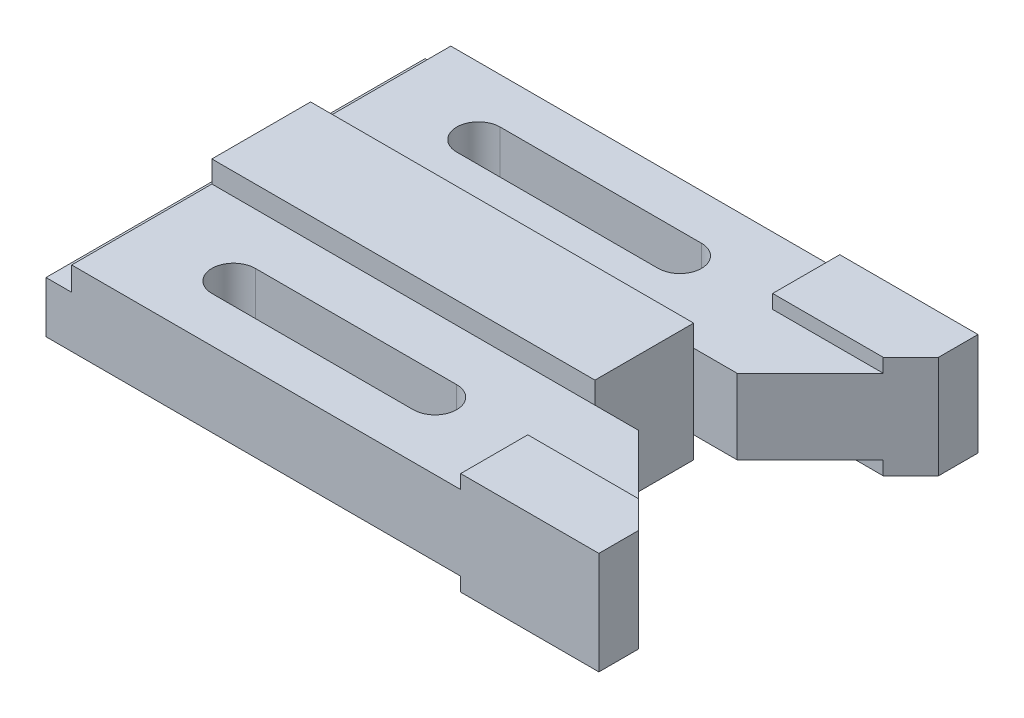
SolidWorks part; units mm, degrees
material "1060 Alloy"
ref_plane "Front Plane" through (0, 0, 0) normal (0, 0, 1) x (1, 0, 0)
ref_plane "Top Plane" through (0, 0, 0) normal (0, 1, 0) x (1, 0, 0)
ref_plane "Right Plane" through (0, 0, 0) normal (1, 0, 0) x (0, 0, -1)
sketch "Sketch2" plane through (0, 0, 0) normal (0, 1, 0) x (1, 0, 0)
  line L0 (0, 0) -> (105, 0) construction
  line L19 (140, 38) -> (114.5, 12.5)
  line L26 (0, -48) -> (0, 48)
  line L27 (0, 48) -> (140, 48)
  line L30 (140, 38) -> (140, 48)
  line L33 (114.5, 12.5) -> (105, 12.5)
  line L35 (105, 12.5) -> (105, -12.5)
  line L36 (140, 0) -> (146.2315, 0) construction
  line L37 (30.5, 31) -> (81.5, 31) construction
  line L38 (140, 48) -> (98, 48)
  line L39 (140, 48) -> (140, 38)
  line L40 (133, 31) -> (98, 31)
  line L41 (98, 48) -> (98, 31)
  line L42 (30.5, 36.5) -> (81.5, 36.5)
  line L43 (30.5, 25.5) -> (81.5, 25.5)
  line L44 (30.5, -31) -> (81.5, -31) construction
  line L45 (30.5, -36.5) -> (81.5, -36.5)
  line L46 (30.5, -25.5) -> (81.5, -25.5)
  line L47 (98, -48) -> (98, -31)
  line L48 (133, -31) -> (98, -31)
  line L49 (140, -38) -> (140, -48)
  line L50 (140, -38) -> (114.5, -12.5)
  line L51 (114.5, -12.5) -> (105, -12.5)
  line L52 (0, -48) -> (140, -48)
  arc A0 (30.5, 36.5) -> (30.5, 25.5) centre (30.5, 31) ccw
  arc A1 (81.5, 25.5) -> (81.5, 36.5) centre (81.5, 31) ccw
  arc A2 (30.5, -36.5) -> (30.5, -25.5) centre (30.5, -31) cw
  arc A3 (81.5, -25.5) -> (81.5, -36.5) centre (81.5, -31) cw
  point P14 (56, 31)
  point P21 (56, -31)
  point P34 (109.75, -12.5)
  dimension "D10" = 51
  dimension "D12" = 10
  dimension "D9" = 5.5
  dimension "D11" = 30.5
  dimension "D17" = 30.5
  dimension "D20" = 36.416
  dimension "D1" = 140
  dimension "D2" = 48
  dimension "D3" = 10
  dimension "D4" = 35
  dimension "D5" = 17
  dimension "D6" = 35.5
  dimension "D7" = 45
  dimension "D8" = 105
  dimension "D13" = 25.5
  dimension "D14" = 9.5
  dimension "D15" = 51
  dimension "D16" = 11.5
  dimension "D18" = 35
  dimension "D19" = 17
  dimension "D21" = 90
  dimension "D22" = 109.75
  dimension "D23" = 98
  dimension "D24" = 62
extrude "Boss-Extrude1" add sketch "Sketch2" along normal blind 30 contours L26 L52 L47 L48 L50 L51 L35 L33 L19 L40 L41 L27 A1 L43 A0 L42 L46 A3 L45 A2 | L27 L41 L40 L19 L30 | L47 L52 L49 L50 L48
sketch "Sketch3" plane through (0, 30, 0) normal (0, 1, 0) x (1, 0, 0)
  line L0 (105, 48) -> (105, 31)
  line L1 (0, 48) -> (140, 48) construction
  line L2 (105, 31) -> (133, 31)
  line L3 (140, 38) -> (114.5, 12.5) construction
  line L4 (133, 31) -> (140, 38)
  line L5 (140, 38) -> (140, 48)
  line L6 (140, 48) -> (105, 48)
  line L7 (0, 0) -> (32.5584, 0) construction
  line L8 (140, -38) -> (140, -48)
  line L9 (140, -48) -> (105, -48)
  line L10 (105, -48) -> (105, -31)
  line L11 (105, -31) -> (133, -31)
  line L12 (133, -31) -> (140, -38)
  dimension "D1" = 35
  dimension "D2" = 17
extrude "Cut-Extrude1" cut sketch "Sketch3" against normal blind 2
sketch "Sketch4" plane through (0, 0, 0) normal (0, -1, 0) x (1, 0, 0)
  line L0 (105, 48) -> (105, 31)
  line L1 (0, 48) -> (140, 48) construction
  line L2 (105, 31) -> (133, 31)
  line L3 (140, 38) -> (114.5, 12.5) construction
  line L4 (133, 31) -> (140, 38)
  line L5 (140, 38) -> (140, 48)
  line L6 (140, 48) -> (105, 48)
  line L7 (0, 0) -> (27.9707, 0) construction
  line L8 (105, -48) -> (105, -31)
  line L9 (140, -48) -> (105, -48)
  line L10 (140, -38) -> (140, -48)
  line L11 (133, -31) -> (140, -38)
  line L12 (105, -31) -> (133, -31)
  dimension "D1" = 35
  dimension "D2" = 17
extrude "Cut-Extrude2" cut sketch "Sketch4" against normal blind 2
sketch "Sketch5" plane through (0, 30, 0) normal (0, 1, 0) x (1, 0, 0)
  line L0 (0, -48) -> (105, -48) construction
  line L1 (0, 48) -> (6.5, 48)
  line L2 (0, 48) -> (0, -48)
  line L3 (0, -48) -> (6.5, -48)
  line L4 (6.5, 48) -> (6.5, -48)
  dimension "D1" = 6.5
extrude "Cut-Extrude3" cut sketch "Sketch5" against normal blind 11.5
sketch "Sketch6" plane through (0, 30, 0) normal (0, 1, 0) x (1, 0, 0)
  line L0 (105, 12.5) -> (6.5, 12.5)
  line L1 (6.5, -48) -> (6.5, 48) construction
  line L2 (105, -12.5) -> (6.5, -12.5)
  line L3 (6.5, -48) -> (6.5, 48) construction
  line L4 (6.5, -12.5) -> (6.5, -48)
  line L5 (6.5, -48) -> (105, -48)
  line L6 (105, -48) -> (105, -31)
  line L7 (105, -31) -> (133, -31)
  line L8 (133, -31) -> (114.5, -12.5)
  line L9 (114.5, -12.5) -> (105, -12.5)
  line L10 (105, 12.5) -> (114.5, 12.5)
  line L11 (114.5, 12.5) -> (133, 31)
  line L12 (133, 31) -> (105, 31)
  line L13 (105, 31) -> (105, 48)
  line L14 (105, 48) -> (6.5, 48)
  line L15 (6.5, 48) -> (6.5, 12.5)
extrude "Cut-Extrude4" cut sketch "Sketch6" against normal blind 5.5
sketch "Sketch7" plane through (0, 0, 0) normal (0, -1, 0) x (1, 0, 0)
  line L0 (105, 12.5) -> (6.5, 12.5)
  line L1 (6.5, 12.5) -> (6.5, -12.5)
  line L2 (6.5, -12.5) -> (105, -12.5)
  line L3 (105, -12.5) -> (114.5, -12.5)
  line L4 (114.5, -12.5) -> (133, -31)
  line L5 (133, -31) -> (105, -31)
  line L6 (105, -31) -> (105, -48)
  line L7 (105, -48) -> (0, -48)
  line L8 (0, -48) -> (0, 48)
  line L9 (0, 48) -> (105, 48)
  line L10 (105, 48) -> (105, 31)
  line L11 (105, 31) -> (133, 31)
  line L12 (133, 31) -> (114.5, 12.5)
  line L13 (114.5, 12.5) -> (105, 12.5)
  dimension "D1" = 6.5
extrude "Cut-Extrude5" cut sketch "Sketch7" against normal blind 5.5
sketch "Sketch8" plane through (105, 0, 0) normal (1, 0, 0) x (0, 0, -1)
  line L1 (-12.5, 30) -> (12.5, 30)
  line L2 (-12.5, 30) -> (-12.5, 0)
  line L3 (-12.5, 0) -> (12.5, 0)
  line L4 (12.5, 30) -> (12.5, 0)
extrude "Cut-Extrude6" cut sketch "Sketch8" against normal blind 1
sketch "Sketch9" plane through (104, 0, 0) normal (1, 0, 0) x (0, 0, -1)
  line L1 (-12.5, 30) -> (12.5, 30)
  line L2 (-12.5, 30) -> (-12.5, 0)
  line L3 (-12.5, 0) -> (12.5, 0)
  line L4 (12.5, 30) -> (12.5, 0)
extrude "Cut-Extrude7" cut sketch "Sketch9" against normal blind 0.5
equation "\"a\"= 140"
equation "\"b\"= 51"
equation "\"c\"= 45deg"
